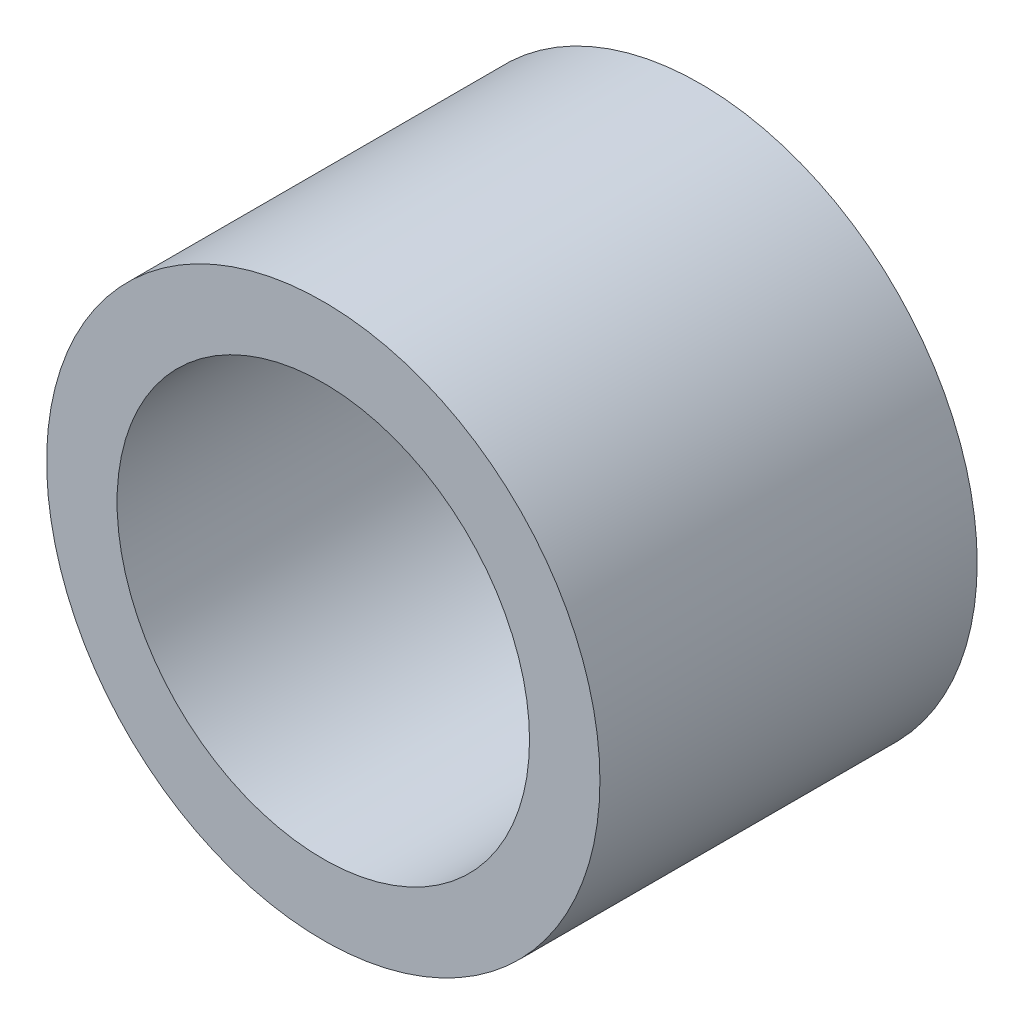
SolidWorks part; units mm, degrees
ref_plane "Front Plane" through (0, 0, 0) normal (0, 0, 1) x (1, 0, 0)
ref_plane "Top Plane" through (0, 0, 0) normal (0, 1, 0) x (1, 0, 0)
ref_plane "Right Plane" through (0, 0, 0) normal (1, 0, 0) x (0, 0, -1)
sketch "Sketch1" plane through (0, 0, 0) normal (0, 0, 1) x (1, 0, 0)
  circle A0 centre (0, 0) radius 5.5
  circle A1 centre (0, 0) radius 4.1
  dimension "D1" = 11
  dimension "D2" = 8.2
extrude "Boss-Extrude1" add sketch "Sketch1" along normal blind 7.5
